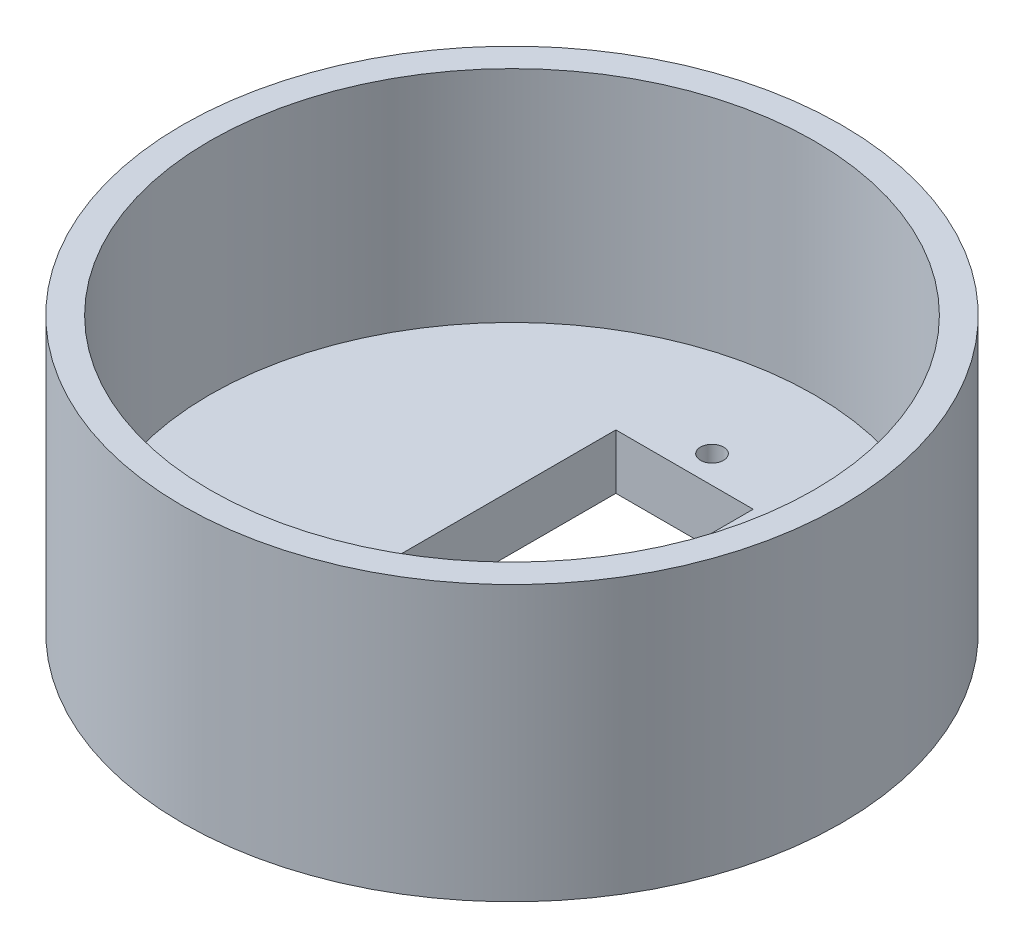
SolidWorks part; units mm, degrees
ref_plane "Front Plane" through (0, 0, 0) normal (0, 0, 1) x (1, 0, 0)
ref_plane "Top Plane" through (0, 0, 0) normal (0, 1, 0) x (1, 0, 0)
ref_plane "Right Plane" through (0, 0, 0) normal (1, 0, 0) x (0, 0, -1)
sketch "Sketch1" plane through (0, 0, 0) normal (0, 1, 0) x (1, 0, 0)
  line L0 (0, 0) -> (0, 31.4) construction
  line L1 (-6.25, 15.7) -> (6.25, 15.7)
  line L2 (-6.25, 15.7) -> (-6.25, -7.5)
  line L3 (-6.25, -7.5) -> (6.25, -7.5)
  line L4 (6.25, 15.7) -> (6.25, -7.5)
  circle A0 centre (0, 0) radius 30
  point P7 (0, -7.5)
  point P9 (0, 15.7)
  dimension "D1" = 60
  dimension "D2" = 23.2
  dimension "D3" = 12.5
  dimension "D4" = 7.5
extrude "Boss-Extrude1" add sketch "Sketch1" along normal blind 5
sketch "Sketch3" plane through (0, 5, 0) normal (0, 1, 0) x (1, 0, 0)
  circle A0 centre (0, 0) radius 4
  dimension "D1" = 8
extrude "Cut-Extrude1" [suppressed] cut sketch "Sketch3" against normal blind 15
sketch "Sketch2" plane through (0, 0, 0) normal (0, -1, 0) x (1, 0, 0)
  line L0 (0, -11.4723) -> (0, 58.5087) construction
  circle A0 centre (0, 45) radius 5
  dimension "D1" = 10
  dimension "D2" = 45
extrude "Boss-Extrude2" [suppressed] add sketch "Sketch2" along normal blind 40
sketch "Sketch4" plane through (0, 5, 0) normal (0, 1, 0) x (1, 0, 0)
  circle A0 centre (0, 0) radius 30
  circle A2 centre (0, 0) radius 30 construction
  circle A3 centre (0, 0) radius 27.5
  dimension "D1" = 2.5
extrude "Boss-Extrude3" add sketch "Sketch4" along normal blind 20
sketch "Sketch5" plane through (0, 5, 0) normal (0, 1, 0) x (1, 0, 0)
  line L0 (0, 20.9719) -> (0, -12.9053) construction
  line L1 (6.25, 15.7) -> (-6.25, 15.7) construction
  line L2 (-6.25, -7.5) -> (6.25, -7.5) construction
  circle A0 centre (0, 18.2) radius 1.05
  circle A1 centre (0, -10) radius 1.05
  dimension "D1" = 2.1
  dimension "D2" = 2.1
  dimension "D3" = 2.5
  dimension "D4" = 2.5
extrude "Cut-Extrude2" cut sketch "Sketch5" against normal up to next
